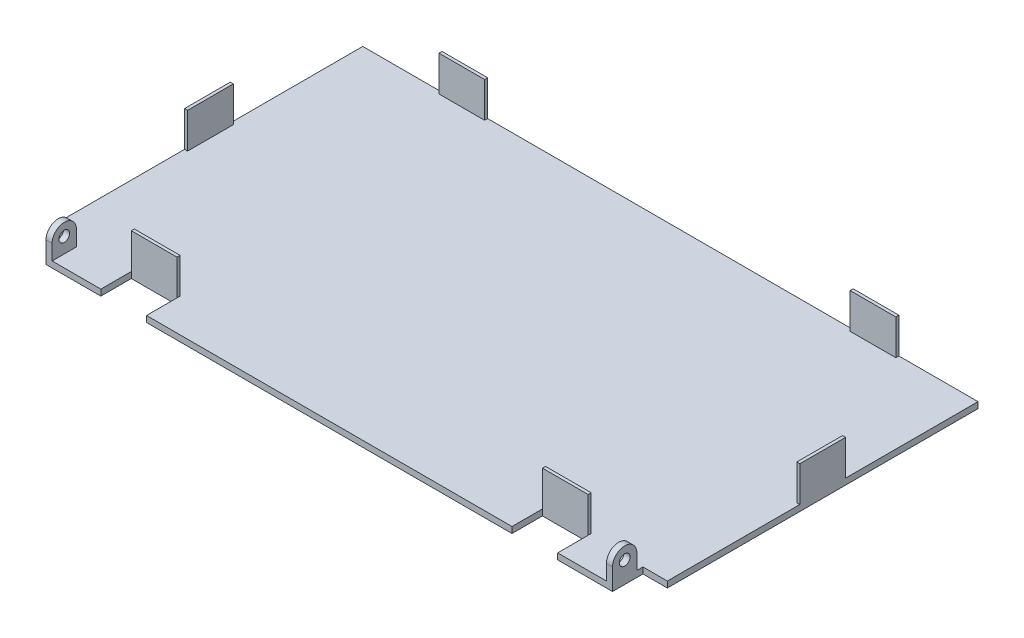
SolidWorks part; units mm, degrees
ref_plane "Front Plane" through (0, 0, 0) normal (0, 0, 1) x (1, 0, 0)
ref_plane "Top Plane" through (0, 0, 0) normal (0, 1, 0) x (1, 0, 0)
ref_plane "Right Plane" through (0, 0, 0) normal (1, 0, 0) x (0, 0, -1)
sketch "Sketch1" plane through (0, 0, 0) normal (0, 1, 0) x (1, 0, 0)
  line L1 (101, -51) -> (-101, -51)
  line L2 (101, -51) -> (101, 51)
  line L3 (101, 51) -> (-101, 51)
  line L4 (-101, -51) -> (-101, 51)
  line L5 (101, -51) -> (-101, 51) construction
  line L6 (101, 51) -> (-101, -51) construction
  point P0 (0, 0)
  dimension "D1" = 102
  dimension "D2" = 202
extrude "Boss-Extrude1" add sketch "Sketch1" along normal blind 2
sketch "Sketch2" plane through (0, 2, 0) normal (0, 1, 0) x (1, 0, 0)
  line L0 (101, 51) -> (-101, 51) construction
  line L1 (-75, 51) -> (-60, 51)
  line L2 (-75, 51) -> (-75, 50)
  line L3 (-75, 50) -> (-60, 50)
  line L4 (-60, 51) -> (-60, 50)
  line L5 (-101, 0) -> (101, 0) construction
  line L6 (-101, 51) -> (-101, -51) construction
  line L7 (101, -51) -> (101, 51) construction
  line L8 (0, 51) -> (0, -51) construction
  line L9 (-101, -51) -> (101, -51) construction
  line L10 (-60, -51) -> (-60, -50)
  line L11 (-75, -50) -> (-60, -50)
  line L12 (-75, -51) -> (-75, -50)
  line L13 (-75, -51) -> (-60, -51)
  line L14 (75, -51) -> (60, -51)
  line L15 (75, -51) -> (75, -50)
  line L16 (75, -50) -> (60, -50)
  line L17 (60, -51) -> (60, -50)
  line L18 (60, 51) -> (60, 50)
  line L19 (75, 50) -> (60, 50)
  line L20 (75, 51) -> (75, 50)
  line L21 (75, 51) -> (60, 51)
  line L22 (100, 7.5) -> (100, -7.5)
  line L23 (-101, 7.5) -> (-100, 7.5)
  line L24 (-101, 7.5) -> (-101, -7.5)
  line L25 (-101, -7.5) -> (-100, -7.5)
  line L26 (-100, 7.5) -> (-100, -7.5)
  line L27 (101, -7.5) -> (100, -7.5)
  line L28 (101, 7.5) -> (101, -7.5)
  line L29 (101, 7.5) -> (100, 7.5)
  point P32 (-100, 0)
  point P37 (100, 0)
  dimension "D1" = 15
  dimension "D2" = 1
  dimension "D3" = 60
  dimension "D4" = 15
  dimension "D5" = 1
extrude "Boss-Extrude2" add sketch "Sketch2" along normal blind 11.6
sketch "Sketch3" plane through (0, 0, 51) normal (0, 0, 1) x (1, 0, 0)
  line L0 (-101, 2) -> (-101, 0) construction
  line L1 (-101, 0) -> (101, 0)
  line L2 (-101, 0) -> (-101, 2)
  line L3 (-101, 2) -> (101, 2)
  line L4 (101, 0) -> (101, 2)
extrude "Boss-Extrude3" add sketch "Sketch3" along normal blind 10
sketch "Sketch9" plane through (0, 2, 0) normal (0, 1, 0) x (1, 0, 0)
  line L0 (0, 51) -> (0, -61) construction
  line L1 (60, 51) -> (-60, 51) construction
  line L2 (101, -61) -> (-101, -61) construction
  line L3 (-101, 51) -> (-101, 7.5) construction
  dimension "D1" = 101
ref_plane "Plane5" through (0, 0, 0) normal (-1, 0, 0) x (0, 0, 1)
sketch "Sketch10" plane through (-101, 0, 0) normal (-1, 0, 0) x (0, 0, 1)
  line L0 (-51, 0) -> (61, 0) construction
  line L1 (61, 2) -> (51, 2)
  line L2 (61, 2) -> (61, 0)
  line L3 (61, 0) -> (51, 0)
  line L4 (51, 2) -> (51, 0)
  dimension "D1" = 10
extrude "Cut-Extrude1" cut sketch "Sketch10" against normal blind 8
mirror "Mirror3" about plane through (0, 0, 0) normal (-1, 0, 0) of "Cut-Extrude1"
sketch "Sketch12" plane through (-93, 0, 0) normal (-1, 0, 0) x (0, 0, 1)
  line L0 (61, 2) -> (61, 7)
  line L1 (61, 2) -> (53, 2)
  line L2 (-51, 2) -> (61, 2) construction
  line L3 (53, 2) -> (53, 7)
  arc A0 (53, 7) -> (61, 7) centre (57, 7) cw
  circle A1 centre (57, 7) radius 1.75
  dimension "D3" = 3.5
  dimension "D1" = 5
  dimension "D2" = 8
extrude "Boss-Extrude5" add sketch "Sketch12" against normal blind 2
mirror "Mirror4" about plane through (0, 0, 0) normal (-1, 0, 0) of "Boss-Extrude5"
sketch "Sketch13" plane through (0, 2, 0) normal (0, 1, 0) x (1, 0, 0)
  line L0 (91, -61) -> (-91, -61) construction
  line L1 (-75, -51) -> (-60, -51)
  line L2 (-75, -51) -> (-75, -61)
  line L3 (-75, -61) -> (-60, -61)
  line L4 (-60, -51) -> (-60, -61)
  line L5 (75, -51) -> (60, -51) construction
  line L6 (60, -51) -> (75, -51)
  line L7 (60, -51) -> (60, -61)
  line L8 (60, -61) -> (75, -61)
  line L9 (75, -51) -> (75, -61)
extrude "Cut-Extrude2" cut sketch "Sketch13" against normal through all
